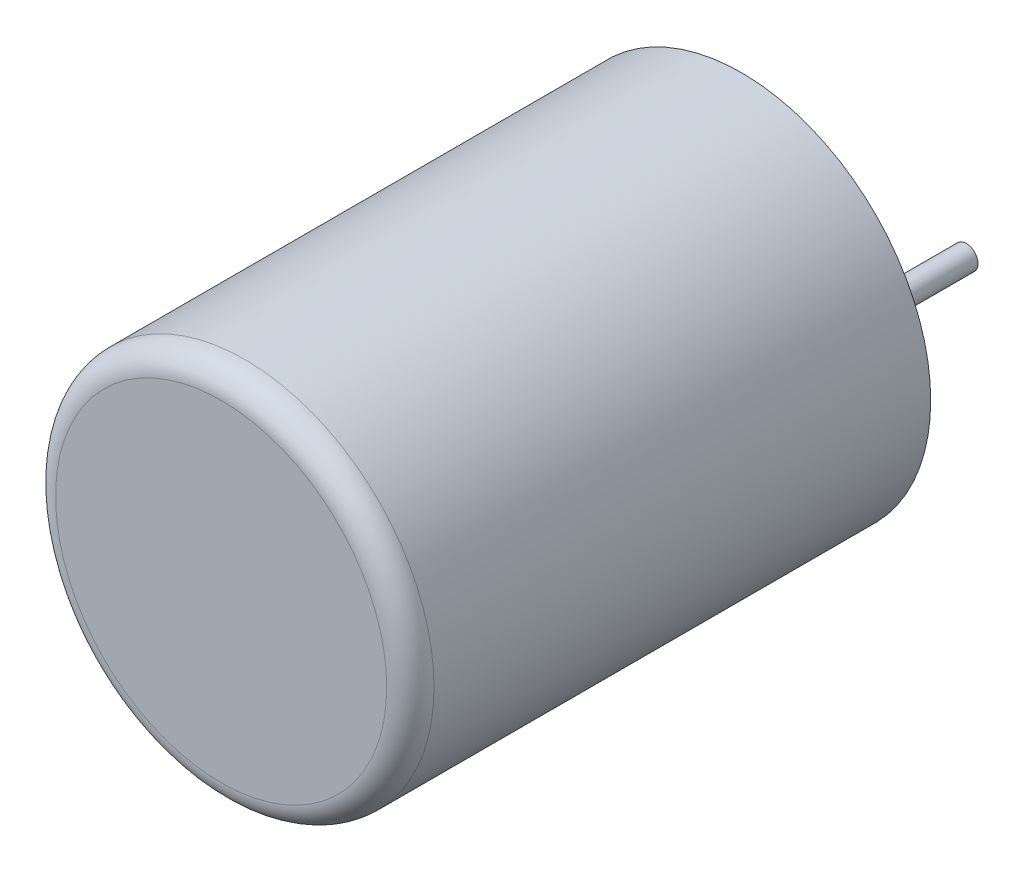
SolidWorks part; units mm, degrees
ref_plane "Спереди" through (0, 0, 0) normal (0, 0, 1) x (1, 0, 0)
ref_plane "Сверху" through (0, 0, 0) normal (0, 1, 0) x (1, 0, 0)
ref_plane "Справа" through (0, 0, 0) normal (1, 0, 0) x (0, 0, -1)
sketch "Эскиз1" plane through (0, 0, 0) normal (0, 0, 1) x (1, 0, 0)
  circle A0 centre (0, 0) radius 4
  dimension "D1" = 8
extrude "Вытянуть1" add sketch "Эскиз1" along normal blind 11
sketch "Эскиз2" plane through (0, 0, 0) normal (0, 0, -1) x (-1, 0, 0)
  line L0 (-8.813, 0) -> (9.6479, 0) construction
  line L1 (0, 0) -> (0, 4.6268) construction
  circle A0 centre (-1.75, 0) radius 0.25
  circle A1 centre (1.75, 0) radius 0.25
  dimension "D1" = 3.5
  dimension "D2" = 0.5
extrude "Вытянуть2" add sketch "Эскиз2" along normal blind 3
fillet "Скругление1" radius 0.5 1 edges at (4, 0, 11)
